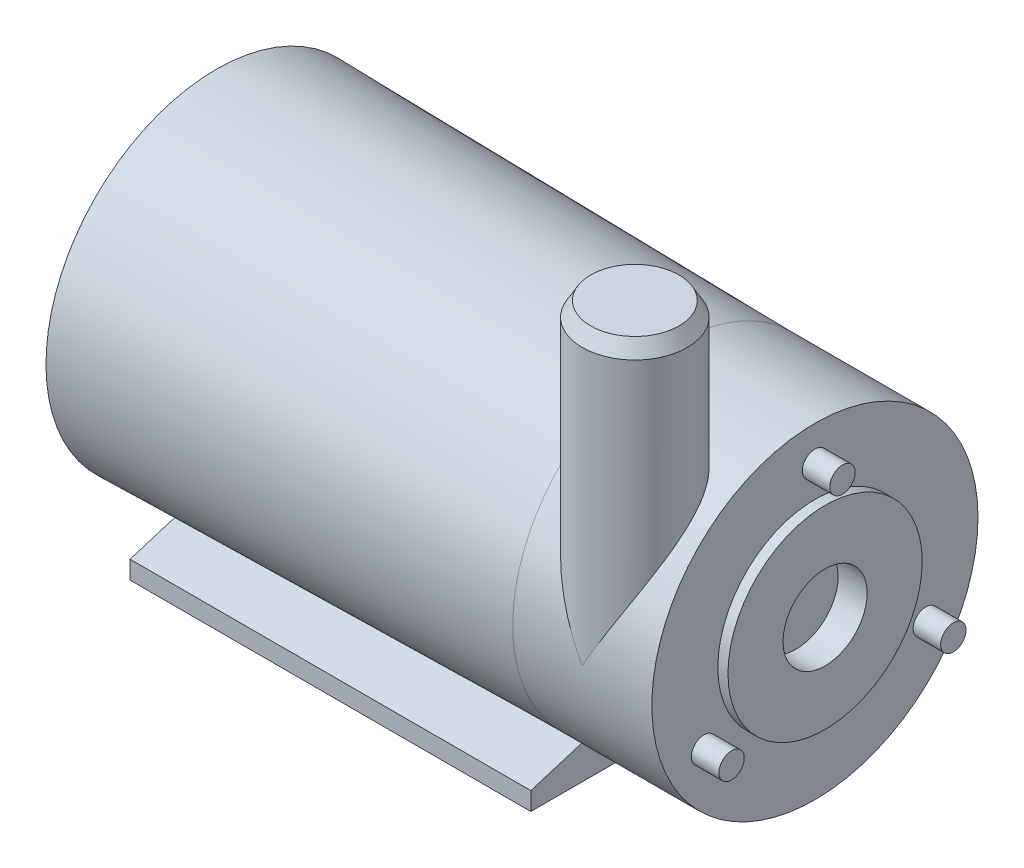
SolidWorks part; units mm, degrees
ref_plane "Front Plane" through (0, 0, 0) normal (0, 0, 1) x (1, 0, 0)
ref_plane "Top Plane" through (0, 0, 0) normal (0, 1, 0) x (1, 0, 0)
ref_plane "Right Plane" through (0, 0, 0) normal (1, 0, 0) x (0, 0, -1)
sketch "Sketch1" plane through (0, 0, 0) normal (1, 0, 0) x (0, 0, -1)
  circle A0 centre (0, 0) radius 11.25
  dimension "D1" = 22.5
extrude "Boss-Extrude1" add sketch "Sketch1" against normal blind 9.6
sketch "Sketch2" plane through (0, 0, 0) normal (0, 1, 0) x (1, 0, 0)
  line L0 (-9.6, -11.25) -> (0, -11.25) construction
  line L1 (-4.8, 11.25) -> (-4.8, -7.625) construction
  line L2 (0, 11.25) -> (-9.6, 11.25) construction
  circle A0 centre (-4.8, -7.625) radius 3.625
  dimension "D1" = 7.25
extrude "Boss-Extrude2" add sketch "Sketch2" along normal blind 20
sketch "Sketch3" plane through (0, 0, 0) normal (1, 0, 0) x (0, 0, -1)
  circle A0 centre (0, 0) radius 6.7
  dimension "D1" = 13.4
extrude "Boss-Extrude3" add sketch "Sketch3" along normal blind 0.7
sketch "Sketch4" plane through (0, 0, 0) normal (1, 0, 0) x (0, 0, -1)
  line L0 (0, 8.8335) -> (0, 0) construction
  line L1 (0, 0) -> (7.65, -4.4167) construction
  line L2 (-7.65, -4.4167) -> (0, 0) construction
  circle A0 centre (0, 8.8335) radius 0.875
  circle A1 centre (7.65, -4.4167) radius 0.875
  circle A2 centre (-7.65, -4.4167) radius 0.875
  dimension "D2" = 1.75
  dimension "D3" = 15.3
  dimension "D1" = 3
extrude "Boss-Extrude4" add sketch "Sketch4" along normal blind 1.9
sketch "Sketch5" plane through (0.7, 0, 0) normal (1, 0, 0) x (0, 0, -1)
  circle A0 centre (0, 0) radius 2.9
  dimension "D1" = 5.8
extrude "Cut-Extrude1" cut sketch "Sketch5" against normal blind 2
sketch "Sketch7" plane through (0, 0, 0) normal (0, 0, 1) x (1, 0, 0)
  line L0 (-9.6, 0) -> (-90.0545, 0) construction
  line L1 (-9.6, 11.25) -> (-9.6, -11.25) construction
  line L2 (-9.6, 0) -> (-9.6, 11.25)
  line L3 (-9.6, 11.25) -> (-41.3, 11.75)
  line L4 (-41.3, 11.75) -> (-41.3, 0)
  line L5 (-41.3, 0) -> (-9.6, 0)
  point P4 (0, 0)
  point P7 (-9.6, 0.0498)
  point P10 (-10.0019, 0.0002)
  point P11 (-9.5534, 0)
  dimension "D1" = 23.5
  dimension "D2" = 31.7
revolve "Revolve1" add sketch "Sketch7" angle 360 about L0
ref_plane "Plane1" through (-9.6, 0, 0) normal (1, 0, 0) x (0, 0, -1)
sketch "Sketch8" plane through (-9.6, 0, 0) normal (1, 0, 0) x (0, 0, -1)
  line L0 (-10, -11.75) -> (10, -11.75)
  line L1 (10, -11.75) -> (10, -10.5)
  line L2 (10, -10.5) -> (3.2169, -8.4099)
  line L3 (3.2169, -8.4099) -> (-3.2169, -8.4099)
  line L4 (-3.2169, -8.4099) -> (-10, -10.5)
  line L5 (-10, -10.5) -> (-10, -11.75)
  line L6 (0, 0) -> (0, -11.75) construction
  circle A0 centre (0, 0) radius 11.75 construction
  point P9 (10, -11.9247)
  point P10 (10, -9.8397)
  point P11 (10, -10.1971)
  point P12 (-3.2169, -8.4099)
  point P13 (0, -11.3248)
  point P14 (0, -11.75)
  dimension "D1" = 20
  dimension "D2" = 1.25
extrude "Boss-Extrude5" add sketch "Sketch8" against normal blind 27.65
chamfer "Chamfer1" distance 1 angle 30 1 edges at (-4.8, 20, 11.25)
